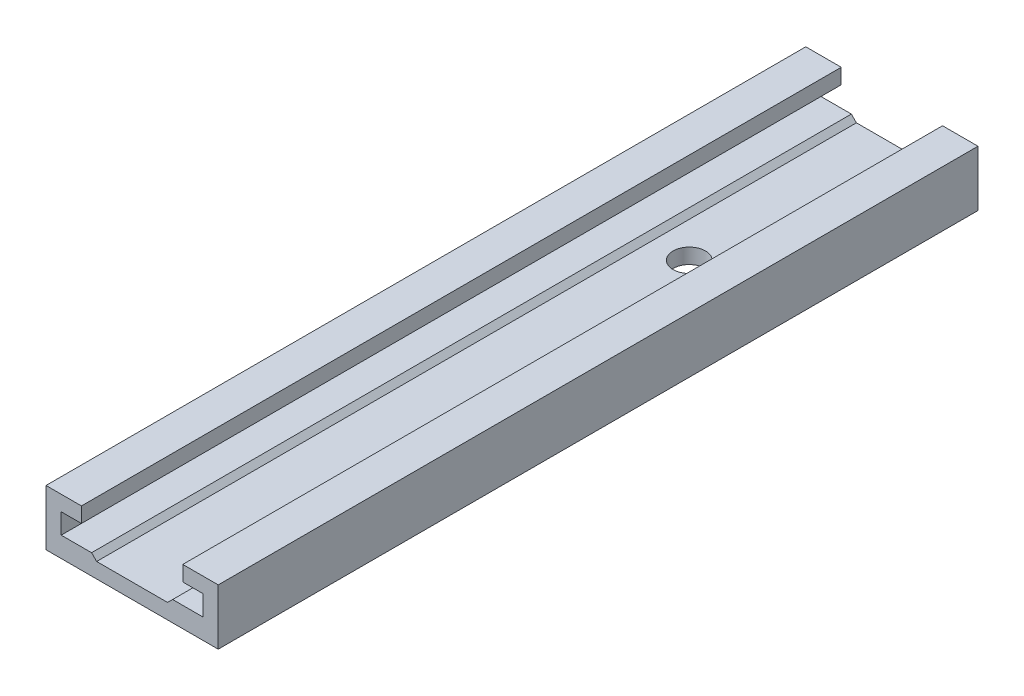
SolidWorks part; units mm, degrees
material "3.3547 (EN-AW 5083)"
ref_plane "Ebene vorne" through (0, 0, 0) normal (0, 0, 1) x (1, 0, 0)
ref_plane "Ebene oben" through (0, 0, 0) normal (0, 1, 0) x (1, 0, 0)
ref_plane "Ebene rechts" through (0, 0, 0) normal (1, 0, 0) x (0, 0, -1)
sketch "Skizze1" plane through (0, 0, 0) normal (0, 0, 1) x (1, 0, 0)
  line L0 (-8.5, 0) -> (8.5, 0)
  line L1 (8.5, 0) -> (8.5, 5.5)
  line L2 (8.5, 5.5) -> (5, 5.5)
  line L3 (5, 5.5) -> (5, 4)
  line L4 (5, 4) -> (7, 4)
  line L5 (7, 4) -> (7, 2)
  line L6 (7, 2) -> (4, 2)
  line L7 (4, 2) -> (3.5, 1.5)
  line L8 (3.5, 1.5) -> (-3.5, 1.5)
  line L9 (-3.5, 1.5) -> (-4, 2)
  line L10 (-4, 2) -> (-7, 2)
  line L11 (-7, 2) -> (-7, 4)
  line L12 (-7, 4) -> (-5, 4)
  line L13 (-5, 4) -> (-5, 5.5)
  line L14 (-5, 5.5) -> (-8.5, 5.5)
  line L15 (-8.5, 5.5) -> (-8.5, 0)
  dimension "D1" = 17
  dimension "D2" = 5.5
  dimension "D3" = 10
  dimension "D4" = 2
  dimension "D5" = 1.5
  dimension "D6" = 1.5
  dimension "D7" = 1.5
  dimension "D8" = 45
  dimension "D9" = 8
extrude "Aufsatz-Linear austragen1" add sketch "Skizze1" along normal blind 75
hole_wizard "Ø3.2 (3.2) Durchmesser Bohrung3" positions "Skizze3" profile "Skizze2" hole size "Ø3.2" standard "DIN" end condition through all
sketch "Skizze3" plane through (0, 1.5, 0) normal (0, 1, 0) x (1, 0, 0)
  line L0 (3.5, 0) -> (-3.5, 0) construction
  line L1 (0, 0) -> (0, -75) construction
  line L2 (3.5, -75) -> (-3.5, -75) construction
  point P0 (0, -80)
  point P2 (0, -20)
  point P11 (0, -140)
  dimension "D1" = 20
  dimension "D2" = 60
  dimension "D3" = 60
sketch "Skizze2" plane through (0, 1.5, 80) normal (1, 0, 0) x (0, 0, 1)
  line L0 (0, 0) -> (0, 1.5)
  line L1 (0, 1.5) -> (1.6, 1.5)
  line L2 (1.6, 1.5) -> (1.6, 0)
  line L5 (1.6, 0) -> (0, 0)
  line L11 (0, -6.35) -> (0, 107.95) construction
  dimension "Bohrerdurchmesser" = 3.2
  dimension "Bohrungstiefe" = 1.5
